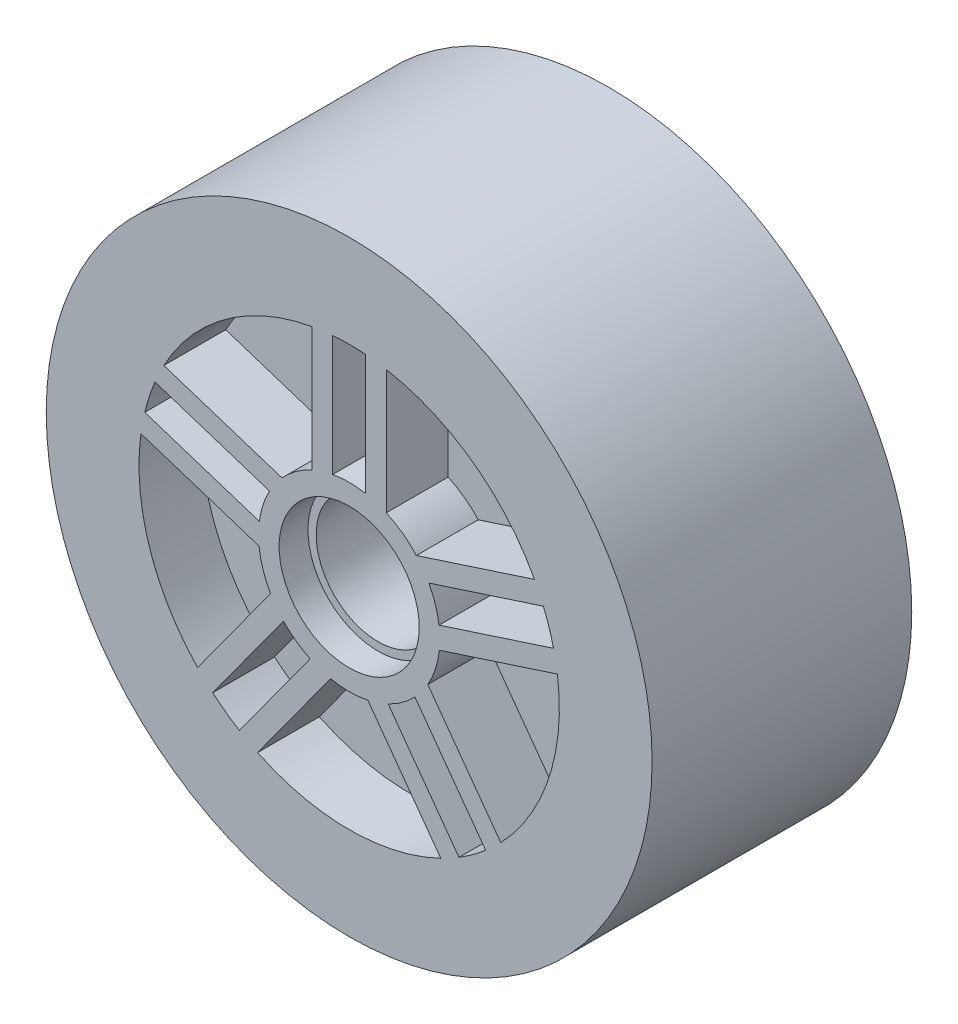
SolidWorks part; units mm, degrees
ref_plane "Front Plane" through (0, 0, 0) normal (0, 0, 1) x (1, 0, 0)
ref_plane "Top Plane" through (0, 0, 0) normal (0, 1, 0) x (1, 0, 0)
ref_plane "Right Plane" through (0, 0, 0) normal (1, 0, 0) x (0, 0, -1)
sketch "Sketch1" plane through (0, 0, 0) normal (0, 0, 1) x (1, 0, 0)
  circle A0 centre (0, 0) radius 5.6
  circle A1 centre (0, 0) radius 1.5
  dimension "D1" = 11.2
  dimension "D2" = 3
extrude "Boss-Extrude1" add sketch "Sketch1" along normal blind 6.3
sketch "Sketch2" plane through (0, 0, 6.3) normal (0, 0, 1) x (1, 0, 0)
  circle A0 centre (0, 0) radius 1.7
  dimension "D1" = 3.4
extrude "Cut-Extrude1" cut sketch "Sketch2" against normal blind 0.7
sketch "Sketch3" plane through (0, 0, 6.3) normal (0, 0, 1) x (1, 0, 0)
  circle A0 centre (0, 0) radius 5.1
  circle A1 centre (0, 0) radius 2.2
  circle A2 centre (0, 0) radius 5.6 construction
  circle A3 centre (0, 0) radius 1.7 construction
  dimension "D1" = 0.5
  dimension "D2" = 0.5
extrude "Cut-Extrude2" cut sketch "Sketch3" against normal blind 1.5
sketch "Sketch4" plane through (0, 0, 4.8) normal (0, 0, 1) x (1, 0, 0)
  line L0 (-0.9, 2.0075) -> (-0.9, 5.02)
  line L1 (-0.4, 5.0843) -> (-0.4, 2.1633)
  line L2 (0.4, 5.0843) -> (0.4, 2.1633)
  line L3 (0.9, 5.02) -> (0.9, 2.0075)
  line L4 (0, 0) -> (0, 7.2862) construction
  line L5 (-0.9, 2.0075) -> (-0.4, 2.0075)
  line L6 (-0.4, 2.0075) -> (-0.4, 2.1633)
  line L7 (0.4, 2.1633) -> (0.4, 2.0075)
  line L8 (0.4, 2.0075) -> (0.9, 2.0075)
  line L9 (0.4, 5.0843) -> (0.9, 5.0843)
  line L10 (0.9, 5.0843) -> (0.9, 5.02)
  line L11 (-0.9, 5.02) -> (-0.9, 5.0843)
  line L12 (-0.9, 5.0843) -> (-0.4, 5.0843)
  line L13 (1.6311, 1.4763) -> (4.4962, 2.4072)
  line L14 (4.7118, 1.9516) -> (1.9338, 1.0489)
  line L15 (4.5573, 2.4271) -> (4.7118, 1.9516)
  line L16 (1.6311, 1.4763) -> (1.7856, 1.0008)
  line L17 (2.0328, 0.2399) -> (2.1873, -0.2356)
  line L18 (4.9591, 1.1907) -> (2.1811, 0.2881)
  line L19 (5.0524, 0.6953) -> (2.1873, -0.2356)
  line L20 (4.9591, 1.1907) -> (5.1136, 0.7152)
  line L21 (4.4962, 2.4072) -> (4.5573, 2.4271)
  line L22 (5.1136, 0.7152) -> (5.0524, 0.6953)
  line L23 (1.7856, 1.0008) -> (1.9338, 1.0489)
  line L24 (2.1811, 0.2881) -> (2.0328, 0.2399)
  line L25 (1.9081, -1.0951) -> (3.6788, -3.5322)
  line L26 (3.3121, -3.8782) -> (1.5952, -1.5151)
  line L27 (3.7166, -3.5843) -> (3.3121, -3.8782)
  line L28 (1.9081, -1.0951) -> (1.5036, -1.389)
  line L29 (0.8564, -1.8592) -> (0.4519, -2.1531)
  line L30 (2.6649, -4.3484) -> (0.948, -1.9853)
  line L31 (2.2225, -4.5902) -> (0.4519, -2.1531)
  line L32 (2.6649, -4.3484) -> (2.2604, -4.6423)
  line L33 (3.6788, -3.5322) -> (3.7166, -3.5843)
  line L34 (2.2604, -4.6423) -> (2.2225, -4.5902)
  line L35 (1.5036, -1.389) -> (1.5952, -1.5151)
  line L36 (0.948, -1.9853) -> (0.8564, -1.8592)
  line L37 (-0.4519, -2.1531) -> (-2.2225, -4.5902)
  line L38 (-2.6649, -4.3484) -> (-0.948, -1.9853)
  line L39 (-2.2604, -4.6423) -> (-2.6649, -4.3484)
  line L40 (-0.4519, -2.1531) -> (-0.8564, -1.8592)
  line L41 (-1.5036, -1.389) -> (-1.9081, -1.0951)
  line L42 (-3.3121, -3.8782) -> (-1.5952, -1.5151)
  line L43 (-3.6788, -3.5322) -> (-1.9081, -1.0951)
  line L44 (-3.3121, -3.8782) -> (-3.7166, -3.5843)
  line L45 (-2.2225, -4.5902) -> (-2.2604, -4.6423)
  line L46 (-3.7166, -3.5843) -> (-3.6788, -3.5322)
  line L47 (-0.8564, -1.8592) -> (-0.948, -1.9853)
  line L48 (-1.5952, -1.5151) -> (-1.5036, -1.389)
  line L49 (-2.1873, -0.2356) -> (-5.0524, 0.6953)
  line L50 (-4.9591, 1.1907) -> (-2.1811, 0.2881)
  line L51 (-5.1136, 0.7152) -> (-4.9591, 1.1907)
  line L52 (-2.1873, -0.2356) -> (-2.0328, 0.2399)
  line L53 (-1.7856, 1.0008) -> (-1.6311, 1.4763)
  line L54 (-4.7118, 1.9516) -> (-1.9338, 1.0489)
  line L55 (-4.4962, 2.4072) -> (-1.6311, 1.4763)
  line L56 (-4.7118, 1.9516) -> (-4.5573, 2.4271)
  line L57 (-5.0524, 0.6953) -> (-5.1136, 0.7152)
  line L58 (-4.5573, 2.4271) -> (-4.4962, 2.4072)
  line L59 (-2.0328, 0.2399) -> (-2.1811, 0.2881)
  line L60 (-1.9338, 1.0489) -> (-1.7856, 1.0008)
  circle A0 centre (0, 0) radius 2.2 construction
  circle A1 centre (0, 0) radius 5.1 construction
  circle A2 centre (0, 0) radius 5.1 construction
  circle A3 centre (0, 0) radius 2.2 construction
  dimension "D1" = 0.4
  dimension "D2" = 0.4
  dimension "D3" = 0.5
  dimension "D4" = 0.5
  dimension "D5" = 5
extrude "Boss-Extrude2" add sketch "Sketch4" along normal blind 1.5
sketch "Sketch5" plane through (0, 0, 0) normal (0, 0, -1) x (-1, 0, 0)
  circle A0 centre (0, 0) radius 2.5
  circle A1 centre (0, 0) radius 1.5 construction
  circle A2 centre (0, 0) radius 4.6
  circle A3 centre (0, 0) radius 5.6 construction
  dimension "D1" = 1
  dimension "D2" = 1
extrude "Cut-Extrude3" cut sketch "Sketch5" against normal blind 1.5
sketch "Sketch6" plane through (0, 0, 6.3) normal (0, 0, 1) x (1, 0, 0)
  circle A0 centre (0, 0) radius 7.35
  circle A1 centre (0, 0) radius 5.6
extrude "Boss-Extrude4" add sketch "Sketch6" against normal blind 6.3
